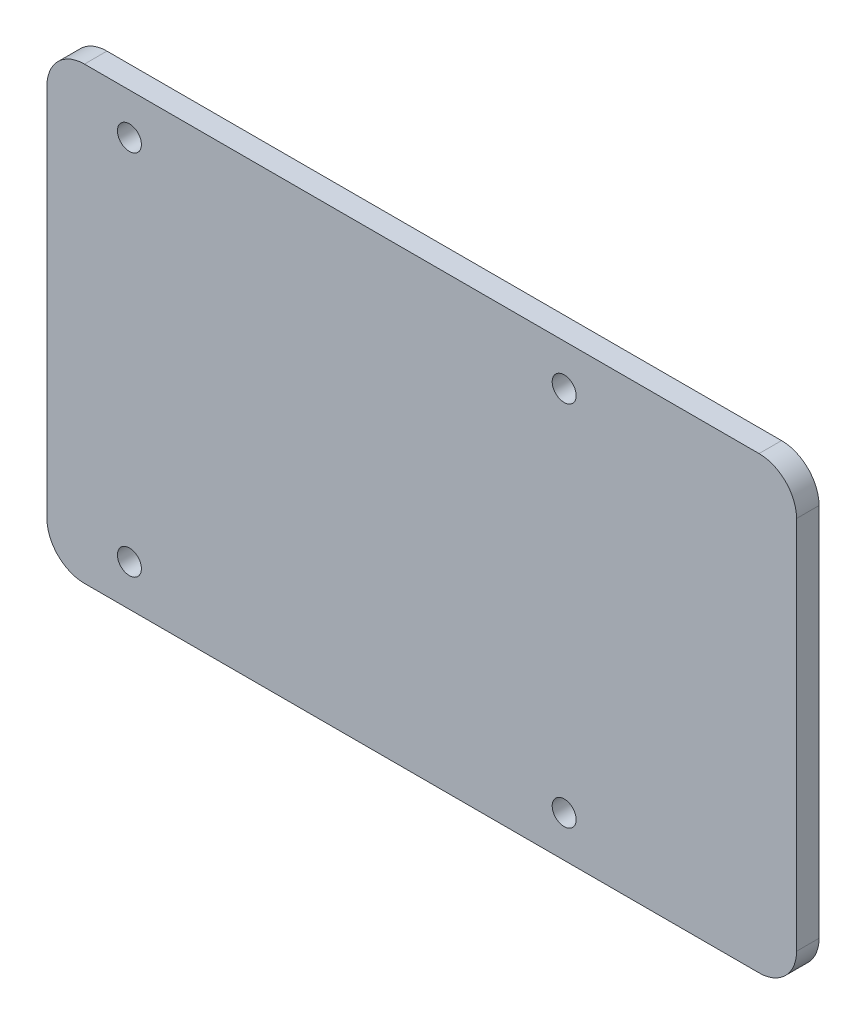
SolidWorks part; units mm, degrees
ref_plane "前视基准面" through (0, 0, 0) normal (0, 0, 1) x (1, 0, 0)
ref_plane "上视基准面" through (0, 0, 0) normal (0, 1, 0) x (1, 0, 0)
ref_plane "右视基准面" through (0, 0, 0) normal (1, 0, 0) x (0, 0, -1)
other "Configuration Table"
sketch "草图1" plane through (0, 0, 0) normal (0, 0, 1) x (1, 0, 0)
  line L0 (-159.4533, 0) -> (191.344, 0) construction
  line L1 (0, 105.0824) -> (0, -113.7085) construction
  line L3 (-45, 30) -> (45, 30)
  line L4 (-50, 25) -> (-50, -25)
  line L5 (-45, -30) -> (45, -30)
  line L6 (50, 25) -> (50, -25)
  circle A0 centre (-39, 24.5) radius 1.6
  circle A1 centre (19, 24.5) radius 1.6
  circle A2 centre (19, -24.5) radius 1.6
  circle A3 centre (-39, -24.5) radius 1.6
  arc A4 (-50, -25) -> (-45, -30) centre (-45, -25) ccw
  arc A5 (45, -30) -> (50, -25) centre (45, -25) ccw
  arc A6 (45, 30) -> (50, 25) centre (45, 25) cw
  arc A7 (-45, 30) -> (-50, 25) centre (-45, 25) ccw
  dimension "D1" = 5
extrude "凸台-拉伸1" add sketch "草图1" along normal blind 3
